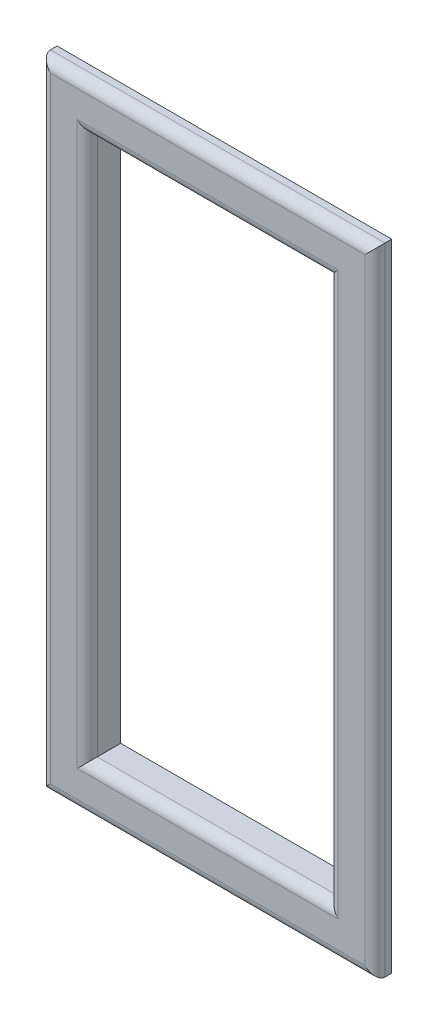
SolidWorks part; units mm, degrees
ref_plane "Alzado" through (0, 0, 0) normal (0, 0, 1) x (1, 0, 0)
ref_plane "Planta" through (0, 0, 0) normal (0, 1, 0) x (1, 0, 0)
ref_plane "Vista lateral" through (0, 0, 0) normal (1, 0, 0) x (0, 0, -1)
sketch "Croquis1" plane through (0, 0, 0) normal (0, 0, 1) x (1, 0, 0)
  line L1 (20, -42.5) -> (-20, -42.5)
  line L2 (20, -42.5) -> (20, 42.5)
  line L3 (20, 42.5) -> (-20, 42.5)
  line L4 (-20, -42.5) -> (-20, 42.5)
  line L5 (20, -42.5) -> (-20, 42.5) construction
  line L6 (20, 42.5) -> (-20, -42.5) construction
  line L7 (18, -40.5) -> (-18, -40.5)
  line L8 (18, -40.5) -> (18, 40.5)
  line L9 (18, 40.5) -> (-18, 40.5)
  line L10 (-18, -40.5) -> (-18, 40.5)
  line L11 (18, -40.5) -> (-18, 40.5) construction
  line L12 (18, 40.5) -> (-18, -40.5) construction
  point P0 (0, 0)
  point P6 (0, 0)
  dimension "D1" = 40
  dimension "D2" = 85
  dimension "D3" = 2
  dimension "D4" = 2
extrude "Saliente-Extruir2" add sketch "Croquis1" along normal mid plane 5
sketch "Croquis2" plane through (0, 0, 0) normal (0, 0, 1) x (1, 0, 0)
  line L1 (20, -42.5) -> (-20, -42.5)
  line L2 (20, -42.5) -> (20, 42.5)
  line L3 (20, 42.5) -> (-20, 42.5)
  line L4 (-20, -42.5) -> (-20, 42.5)
  line L5 (20, -42.5) -> (-20, 42.5) construction
  line L6 (20, 42.5) -> (-20, -42.5) construction
  line L7 (25, -47.5) -> (-25, -47.5)
  line L8 (25, -47.5) -> (25, 47.5)
  line L9 (25, 47.5) -> (-25, 47.5)
  line L10 (-25, -47.5) -> (-25, 47.5)
  line L11 (25, -47.5) -> (-25, 47.5) construction
  line L12 (25, 47.5) -> (-25, -47.5) construction
  point P0 (0, 0)
  point P7 (0, 0)
  dimension "D1" = 5
  dimension "D2" = 5
extrude "Saliente-Extruir3" add sketch "Croquis2" along normal blind 2.5
fillet "Redondeo1" radius 1.5 8 edges at (0, -40.5, 2.5) (18, 0, 2.5) (-18, 0, 2.5) (0, 40.5, 2.5) (0, 47.5, 2.5) (25, 0, 2.5) (-25, 0, 2.5) (0, -47.5, 2.5)
